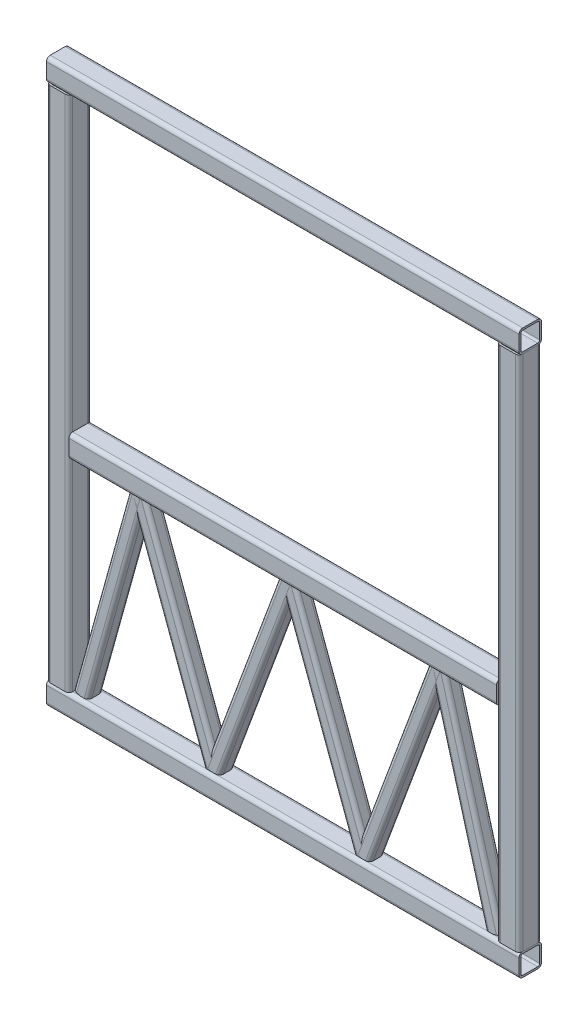
SolidWorks part; units mm, degrees
other "Weld Folder"
material "Plain Carbon Steel"
ref_plane "Front Plane" through (0, 0, 0) normal (0, 0, 1) x (1, 0, 0)
ref_plane "Top Plane" through (0, 0, 0) normal (0, 1, 0) x (1, 0, 0)
ref_plane "Right Plane" through (0, 0, 0) normal (1, 0, 0) x (0, 0, -1)
sketch "Sketch1" plane through (0, 0, 0) normal (0, 0, 1) x (1, 0, 0)
  line L0 (0, 0) -> (1524, 0)
  line L1 (1460.5, 38.1) -> (1270, 723.9)
  line L2 (1270, 723.9) -> (1016, 38.1)
  line L3 (1016, 38.1) -> (762, 723.9)
  line L4 (762, 723.9) -> (508, 38.1)
  line L5 (508, 38.1) -> (254, 723.9)
  line L6 (254, 723.9) -> (63.5, 38.1)
  line L7 (0, 723.9) -> (1524, 723.9) construction
  line L8 (1524, 0) -> (1524, 1828.8)
  line L9 (1524, 1828.8) -> (0, 1828.8)
  line L10 (0, 1828.8) -> (0, 0)
  line L11 (38.1, 723.9) -> (38.1, 38.1) construction
  line L12 (38.1, 38.1) -> (1485.9, 38.1) construction
  line L13 (1485.9, 38.1) -> (1485.9, 723.9) construction
  line L14 (1485.9, 38.1) -> (1524, 38.1) construction
  line L15 (38.1, 38.1) -> (0, 38.1) construction
  line L16 (38.1, 38.1) -> (38.1, 0) construction
  line L17 (38.1, 38.1) -> (63.5, 38.1) construction
  line L18 (1485.9, 38.1) -> (1460.5, 38.1) construction
  line L19 (762, 723.9) -> (762, 0) construction
  line L20 (0, 762) -> (1524, 762)
  dimension "D1" = 1524
  dimension "D2" = 38.1
  dimension "D3" = 1828.8
  dimension "D4" = 38.1
  dimension "D5" = 25.4
  dimension "D6" = 1016
  dimension "D7" = 762
ref_plane "Plane5" through (1524, 0, 0) normal (1, 0, 0) x (0, 0, -1)
other "Structural Member5"
ref_plane "Plane7" through (0, 0, 0) normal (1, 0, 0) x (0, 1, 0)
sketch "Sketch111" plane through (0, 0, 0) normal (1, 0, 0) x (0, 1, 0)
  line L0 (-25.4, -31.75) -> (25.4, -31.75)
  line L1 (-31.75, -25.4) -> (-31.75, 25.4)
  line L2 (25.4, 31.75) -> (-25.4, 31.75)
  line L3 (31.75, 25.4) -> (31.75, -25.4)
  line L4 (-25.4, -38.1) -> (25.4, -38.1)
  line L5 (-38.1, -25.4) -> (-38.1, 25.4)
  line L6 (25.4, 38.1) -> (-25.4, 38.1)
  line L7 (38.1, 25.4) -> (38.1, -25.4)
  line L8 (0, 0) -> (31.75, 0) construction
  line L9 (0, 0) -> (0, 31.75) construction
  arc A0 (38.1, 25.4) -> (25.4, 38.1) centre (25.4, 25.4) ccw
  arc A1 (25.4, -38.1) -> (38.1, -25.4) centre (25.4, -25.4) ccw
  arc A2 (-38.1, -25.4) -> (-25.4, -38.1) centre (-25.4, -25.4) ccw
  arc A3 (-25.4, 38.1) -> (-38.1, 25.4) centre (-25.4, 25.4) ccw
  arc A4 (-25.4, 31.75) -> (-31.75, 25.4) centre (-25.4, 25.4) ccw
  arc A5 (31.75, 25.4) -> (25.4, 31.75) centre (25.4, 25.4) ccw
  arc A6 (25.4, -31.75) -> (31.75, -25.4) centre (25.4, -25.4) ccw
  arc A7 (-31.75, -25.4) -> (-25.4, -31.75) centre (-25.4, -25.4) ccw
  point P3 (0, 38.1)
  point P4 (38.1, 0)
  point P5 (0, -38.1)
  point P6 (-38.1, 0)
  point P7 (-38.1, 38.1)
  point P8 (-38.1, -38.1)
  point P33 (0, 0)
  point P35 (38.1, -38.1)
  point P36 (38.1, 38.1)
  point P37 (0, 0)
  dimension "D1" = 12.7
  dimension "Thickness" = 6.35
  dimension "V_leg" = 76.2
sketch "Sketch115" plane through (0, 0, 0) normal (0, 0, 1) x (1, 0, 0)
  line L2 (254, 723.9) -> (63.5, 38.1) construction
  line L3 (508, 38.1) -> (254, 723.9) construction
  line L5 (762, 723.9) -> (508, 38.1) construction
  line L6 (1016, 38.1) -> (762, 723.9) construction
  line L7 (1270, 723.9) -> (1016, 38.1) construction
  line L8 (1460.5, 38.1) -> (1270, 723.9) construction
  line L9 (254, 723.9) -> (63.5, 38.1)
  line L10 (508, 38.1) -> (254, 723.9)
  line L11 (762, 723.9) -> (508, 38.1)
  line L12 (1016, 38.1) -> (762, 723.9)
  line L13 (1270, 723.9) -> (1016, 38.1)
  line L14 (1460.5, 38.1) -> (1270, 723.9)
other "Structural Member6"
ref_plane "Plane9" through (254, 723.9, 0) normal (-0.2676, -0.9635, 0) x (0.9635, -0.2676, 0)
sketch "Sketch113" plane through (254, 723.9, 0) normal (-0.2676, -0.9635, 0) x (0.9635, -0.2676, 0)
  line L0 (-12.7, -19.05) -> (12.7, -19.05)
  line L1 (-19.05, -12.7) -> (-19.05, 12.7)
  line L2 (12.7, 19.05) -> (-12.7, 19.05)
  line L3 (19.05, 12.7) -> (19.05, -12.7)
  line L4 (-12.7, -25.4) -> (12.7, -25.4)
  line L5 (-25.4, -12.7) -> (-25.4, 12.7)
  line L6 (12.7, 25.4) -> (-12.7, 25.4)
  line L7 (25.4, 12.7) -> (25.4, -12.7)
  line L8 (0, 0) -> (19.05, 0) construction
  line L9 (0, 0) -> (0, 19.05) construction
  arc A0 (25.4, 12.7) -> (12.7, 25.4) centre (12.7, 12.7) ccw
  arc A1 (12.7, -25.4) -> (25.4, -12.7) centre (12.7, -12.7) ccw
  arc A2 (-25.4, -12.7) -> (-12.7, -25.4) centre (-12.7, -12.7) ccw
  arc A3 (-12.7, 25.4) -> (-25.4, 12.7) centre (-12.7, 12.7) ccw
  arc A4 (-12.7, 19.05) -> (-19.05, 12.7) centre (-12.7, 12.7) ccw
  arc A5 (19.05, 12.7) -> (12.7, 19.05) centre (12.7, 12.7) ccw
  arc A6 (12.7, -19.05) -> (19.05, -12.7) centre (12.7, -12.7) ccw
  arc A7 (-19.05, -12.7) -> (-12.7, -19.05) centre (-12.7, -12.7) ccw
  point P3 (0, 25.4)
  point P4 (25.4, 0)
  point P5 (0, -25.4)
  point P6 (-25.4, 0)
  point P7 (-25.4, 25.4)
  point P8 (-25.4, -25.4)
  point P33 (0, 0)
  point P35 (25.4, -25.4)
  point P36 (25.4, 25.4)
  point P37 (0, 0)
  dimension "D1" = 12.7
  dimension "Thickness" = 6.35
  dimension "V_leg" = 50.8
